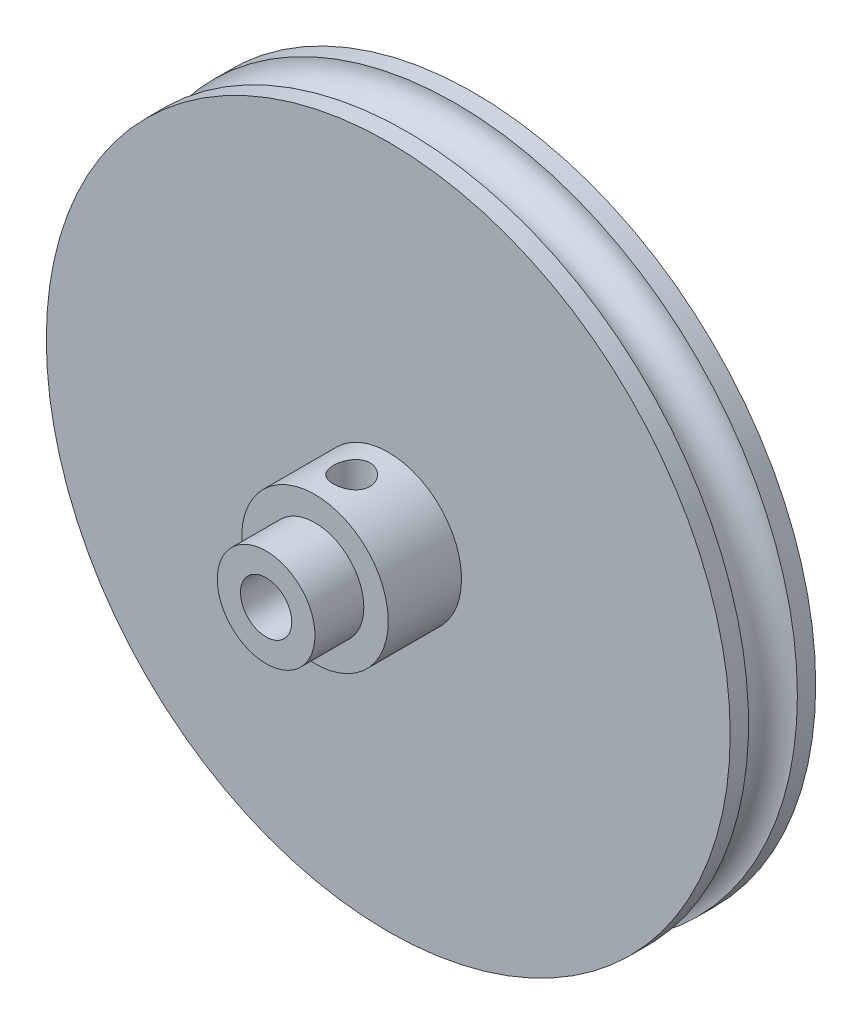
SolidWorks part; units mm, degrees
ref_plane "Plan de face" through (0, 0, 0) normal (0, 0, 1) x (1, 0, 0)
ref_plane "Plan de dessus" through (0, 0, 0) normal (0, 1, 0) x (1, 0, 0)
ref_plane "Plan de droite" through (0, 0, 0) normal (1, 0, 0) x (0, 0, -1)
sketch "Esquisse1" plane through (0, 0, 0) normal (0, 0, 1) x (1, 0, 0)
  circle A0 centre (0, 0) radius 28
  dimension "D1" = 56
extrude "Boss.-Extru.1" add sketch "Esquisse1" along normal blind 7
sketch "Esquisse2" plane through (0, 0, 7) normal (0, 0, 1) x (1, 0, 0)
  circle A0 centre (0, 0) radius 4
extrude "Boss.-Extru.2" add sketch "Esquisse2" along normal blind 10
sketch "Esquisse3" plane through (0, 0, 17) normal (0, 0, 1) x (1, 0, 0)
  circle A0 centre (0, 0) radius 2.1
  dimension "D1" = 4.2
extrude "Enlèv. mat.-Extru.1" cut sketch "Esquisse3" against normal through all
sketch "Esquisse4" plane through (0, 0, 0) normal (1, 0, 0) x (0, 0, -1)
  line L0 (-3.5, 28) -> (-3.5, 8.0945) construction
  line L1 (0, 28) -> (-7, 28) construction
  line L2 (0, 0) -> (-21.8888, 0) construction
  line L3 (-3.5, 0) -> (-3.5, -28) construction
  circle A1 centre (-3.5, 28) radius 2
  circle A2 centre (-3.5, -28) radius 2 construction
  dimension "D1" = 4
revolve "Enlèvement de matière-Révolution1" cut sketch "Esquisse4" angle 360 about L2
sketch "Esquisse5" plane through (0, 0, 7) normal (0, 0, 1) x (1, 0, 0)
  circle A0 centre (0, 0) radius 4
  circle A1 centre (0, 0) radius 6
extrude "Boss.-Extru.3" add sketch "Esquisse5" along normal blind 6
sketch "Esquisse6" plane through (0, 0, 0) normal (0, 1, 0) x (1, 0, 0)
  line L0 (0, -13) -> (0, -7) construction
  line L1 (-4, -13) -> (4, -13) construction
  line L2 (-6, -7) -> (6, -7) construction
  circle A0 centre (0, -10) radius 1.5
extrude "Enlèv. mat.-Extru.2" cut sketch "Esquisse6" along normal up to next
